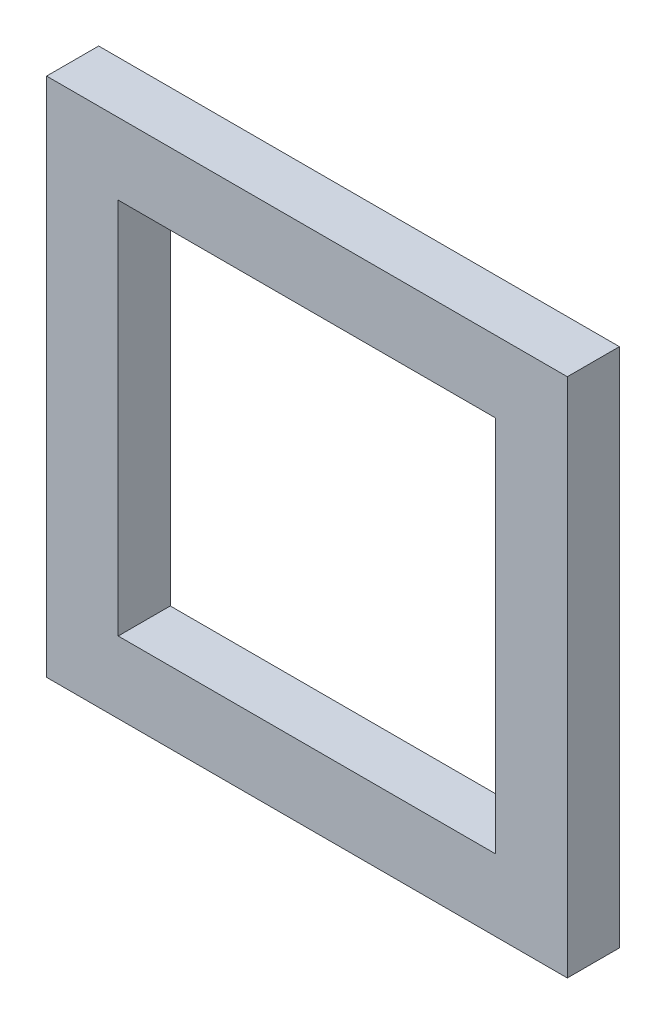
SolidWorks part; units mm, degrees
material "Balsa"
ref_plane "Front Plane" through (0, 0, 0) normal (0, 0, 1) x (1, 0, 0)
ref_plane "Top Plane" through (0, 0, 0) normal (0, 1, 0) x (1, 0, 0)
ref_plane "Right Plane" through (0, 0, 0) normal (1, 0, 0) x (0, 0, -1)
sketch "Sketch1" plane through (0, 0, 0) normal (0, 0, 1) x (1, 0, 0)
  line L1 (-63.5, -63.5) -> (63.5, -63.5)
  line L2 (-63.5, -63.5) -> (-63.5, 63.5)
  line L3 (-63.5, 63.5) -> (63.5, 63.5)
  line L4 (63.5, -63.5) -> (63.5, 63.5)
  line L5 (-63.5, -63.5) -> (63.5, 63.5) construction
  line L6 (-63.5, 63.5) -> (63.5, -63.5) construction
  line L7 (-46.0375, -46.0375) -> (46.0375, -46.0375)
  line L8 (-46.0375, -46.0375) -> (-46.0375, 46.0375)
  line L9 (-46.0375, 46.0375) -> (46.0375, 46.0375)
  line L10 (46.0375, -46.0375) -> (46.0375, 46.0375)
  line L11 (-46.0375, -46.0375) -> (46.0375, 46.0375) construction
  line L12 (-46.0375, 46.0375) -> (46.0375, -46.0375) construction
  point P0 (0, 0)
  point P6 (0, 0)
  dimension "D1" = 127
  dimension "D2" = 127
  dimension "D3" = 17.4625
extrude "Boss-Extrude1" add sketch "Sketch1" against normal blind 12.7
ref_plane "Plane1" through (0, 63.5, 0) normal (0, 1, 0) x (1, 0, 0)
ref_plane "Plane2" through (0, 0, 0) normal (0, 1, 0) x (1, 0, 0)
